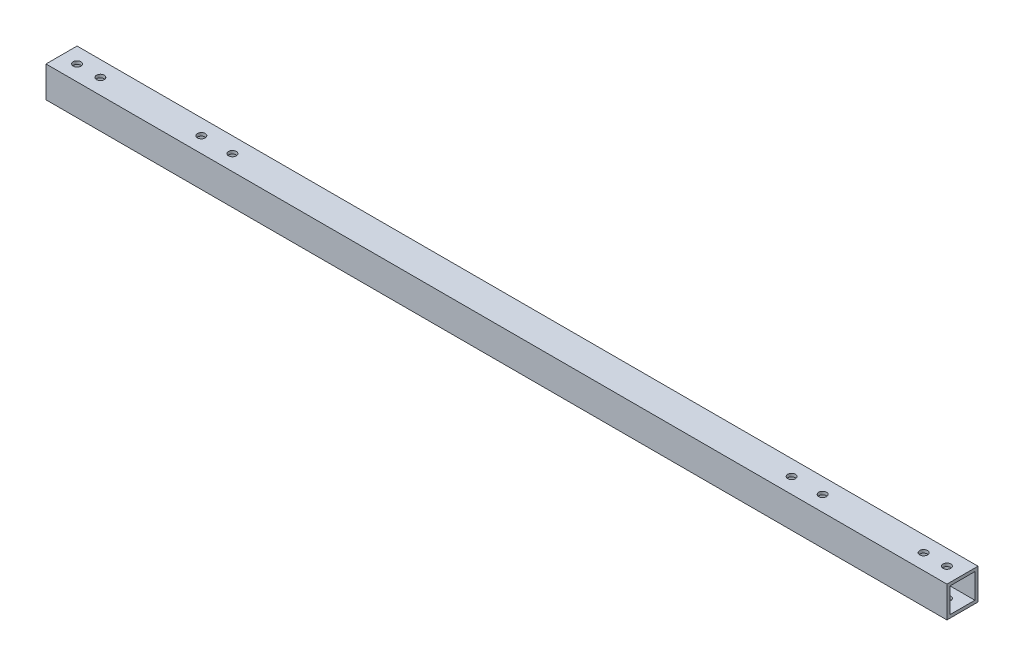
SolidWorks part; units mm, degrees
material "1345 Alloy"
ref_plane "Front Plane" through (0, 0, 0) normal (0, 0, 1) x (1, 0, 0)
ref_plane "Top Plane" through (0, 0, 0) normal (0, 1, 0) x (1, 0, 0)
ref_plane "Right Plane" through (0, 0, 0) normal (1, 0, 0) x (0, 0, -1)
sketch "Sketch1" plane through (0, 0, 0) normal (1, 0, 0) x (0, 0, -1)
  line L1 (-10, 10) -> (10, 10)
  line L2 (-10, 10) -> (-10, -10)
  line L3 (-10, -10) -> (10, -10)
  line L4 (10, 10) -> (10, -10)
  line L5 (-10, 10) -> (10, -10) construction
  line L6 (-10, -10) -> (10, 10) construction
  line L7 (-8, 8) -> (8, 8)
  line L8 (-8, 8) -> (-8, -8)
  line L9 (-8, -8) -> (8, -8)
  line L10 (8, 8) -> (8, -8)
  line L11 (-8, 8) -> (8, -8) construction
  line L12 (-8, -8) -> (8, 8) construction
  point P0 (0, 0)
  point P6 (0, 0)
  dimension "D1" = 20
  dimension "D2" = 20
  dimension "D3" = 16
  dimension "D4" = 16
extrude "Boss-Extrude1" add sketch "Sketch1" along normal blind 580
sketch "Sketch2" plane through (0, 10, 0) normal (0, 1, 0) x (1, 0, 0)
  line L0 (-16.9319, 0) -> (495.2657, 0) construction
  line L1 (580, 10) -> (580, -10) construction
  line L2 (0, 10) -> (0, -10) construction
  line L3 (10, 31.8777) -> (10, -17.8515) construction
  line L4 (570, 25.7534) -> (570, -31.8149) construction
  circle A0 centre (10, 0) radius 2.5
  circle A1 centre (570, 0) radius 2.5
  circle A3 centre (25, 0) radius 2.5
  circle A4 centre (555, 0) radius 2.5
  dimension "D1" = 5
  dimension "D2" = 5
  dimension "D7" = 15
  dimension "D3" = 10
  dimension "D4" = 10
  dimension "D8" = 15
  dimension "D5" = 2
  dimension "D6" = 2
extrude "Cut-Extrude1" cut sketch "Sketch2" against normal through all
sketch "Sketch3" plane through (0, 10, 0) normal (0, 1, 0) x (1, 0, 0)
  line L0 (-18.446, 0) -> (591.1979, 0) construction
  line L1 (0, 10) -> (0, -10) construction
  line L2 (290, 10) -> (290, -84.2137) construction
  line L3 (580, 10) -> (0, 10) construction
  circle A0 centre (110, 0) radius 2.5
  circle A1 centre (90, 0) radius 2.5
  circle A2 centre (490, 0) radius 2.5
  circle A3 centre (470, 0) radius 2.5
  dimension "D1" = 5
  dimension "D2" = 5
  dimension "D3" = 20
  dimension "D4" = 110
extrude "Cut-Extrude2" cut sketch "Sketch3" against normal through all
